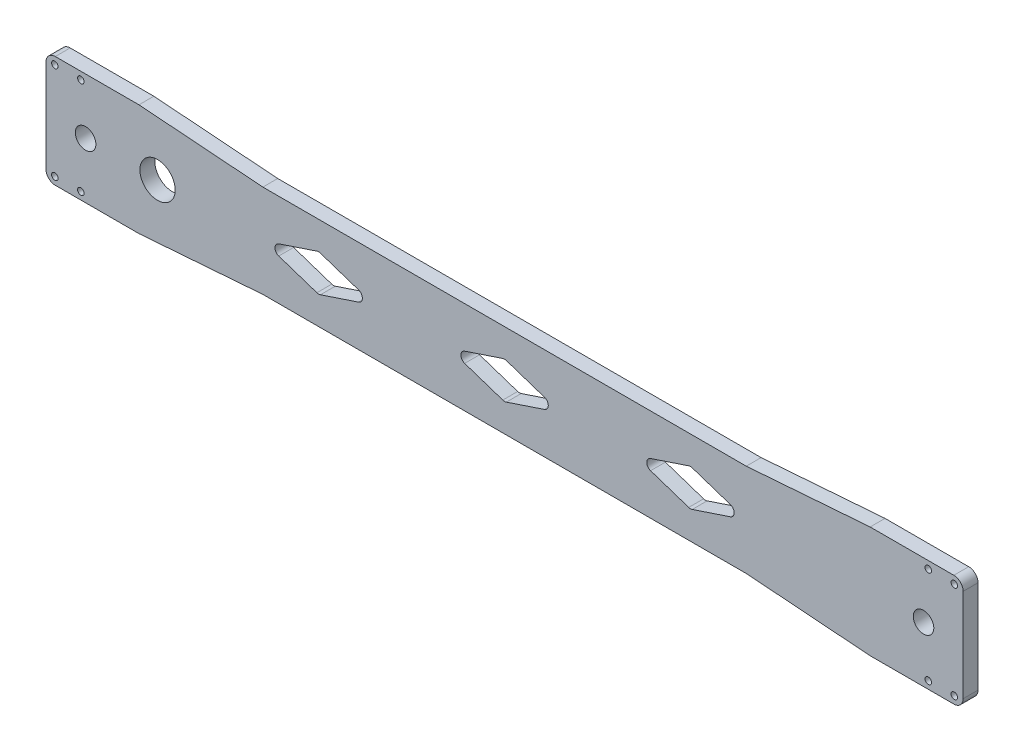
SolidWorks part; units mm, degrees
ref_plane "前视基准面" through (0, 0, 0) normal (0, 0, 1) x (1, 0, 0)
ref_plane "上视基准面" through (0, 0, 0) normal (0, 1, 0) x (1, 0, 0)
ref_plane "右视基准面" through (0, 0, 0) normal (1, 0, 0) x (0, 0, -1)
other "Configuration Table"
sketch "草图1" plane through (0, 0, 0) normal (0, 0, 1) x (1, 0, 0)
  line L0 (246.65, 5) -> (246.65, -55) construction
  line L1 (0, 0) -> (50, 0)
  line L2 (0, 0) -> (0, -60)
  line L3 (0, -60) -> (50, -60)
  line L4 (493.3, 0) -> (493.3, -60)
  line L5 (50, 0) -> (116.65, -5)
  line L6 (116.65, -5) -> (376.65, -5)
  line L7 (376.65, -5) -> (443.3, 0)
  line L8 (443.3, 0) -> (493.3, 0)
  line L9 (0, -30) -> (493.3, -30) construction
  line L10 (376.65, -55) -> (443.3, -60)
  line L11 (116.65, -55) -> (376.65, -55)
  line L12 (50, -60) -> (116.65, -55)
  line L13 (443.3, -60) -> (493.3, -60)
  line L14 (116.65, -30) -> (146.65, -20)
  line L15 (116.65, -30) -> (146.65, -40)
  line L16 (146.65, -20) -> (176.65, -30)
  line L17 (146.65, -40) -> (176.65, -30)
  line L18 (216.65, -30) -> (246.65, -20)
  line L19 (216.65, -30) -> (246.65, -40)
  line L20 (246.65, -40) -> (276.65, -30)
  line L21 (246.65, -20) -> (276.65, -30)
  line L22 (316.65, -30) -> (346.65, -20)
  line L23 (316.65, -30) -> (346.65, -40)
  line L24 (346.65, -40) -> (376.65, -30)
  line L25 (346.65, -20) -> (376.65, -30)
  dimension "D1" = 60
  dimension "D2" = 493.3
  dimension "D3" = 50
  dimension "D4" = 50
  dimension "D5" = 260
  dimension "D6" = 130
  dimension "D7" = 5
  dimension "D8" = 66.65
  dimension "D9" = 70
  dimension "D10" = 30
  dimension "D11" = 20
  dimension "D12" = 3
extrude "凸台-拉伸1" add sketch "草图1" along normal blind 8
fillet "圆角1" radius 3 12 edges at (146.65, -40, 4) (176.65, -30, 4) (116.65, -30, 4) (146.65, -20, 4) (316.65, -30, 4) (346.65, -20, 4) (376.65, -30, 4) (346.65, -40, 4) (246.65, -40, 4) (276.65, -30, 4) (216.65, -30, 4) (246.65, -20, 4)
fillet "圆角2" radius 5 4 edges at (493.3, -60, 4) (493.3, 0, 4) (0, -60, 4) (0, 0, 4)
sketch "草图2" plane through (0, 0, 8) normal (0, 0, 1) x (1, 0, 0)
  line L0 (0, -5) -> (0, -55) construction
  line L1 (50, 0) -> (5, 0) construction
  line L2 (0, -30) -> (23.1554, -30) construction
  line L3 (246.65, -5) -> (246.65, -55) construction
  line L4 (376.65, -5) -> (116.65, -5) construction
  line L5 (116.65, -55) -> (376.65, -55) construction
  circle A0 centre (4.75, -4) radius 1.75
  circle A1 centre (18.75, -4) radius 1.75
  circle A2 centre (18.75, -56) radius 1.75
  circle A3 centre (4.75, -56) radius 1.75
  circle A4 centre (21.3, -30) radius 5.525
  circle A5 centre (488.55, -4) radius 1.75
  circle A6 centre (474.55, -4) radius 1.75
  circle A7 centre (474.55, -56) radius 1.75
  circle A8 centre (488.55, -56) radius 1.75
  circle A9 centre (472, -30) radius 5.525
  dimension "D3" = 3.5
  dimension "D6" = 11.05
  dimension "D1" = 4.75
  dimension "D2" = 4
  dimension "D7" = 21.3
  dimension "D4" = 2
  dimension "D5" = 2
extrude "切除-拉伸1" cut sketch "草图2" against normal blind 10
sketch "草图3" plane through (0, 0, 8) normal (0, 0, 1) x (1, 0, 0)
  line L0 (493.3, -30) -> (413.1349, -30) construction
  line L1 (493.3, -55) -> (493.3, -5) construction
  line L2 (0, -5) -> (0, -55) construction
  circle A0 centre (60, -30) radius 9.5
  dimension "D1" = 19
  dimension "D2" = 60
extrude "切除-拉伸2" cut sketch "草图3" against normal through all
